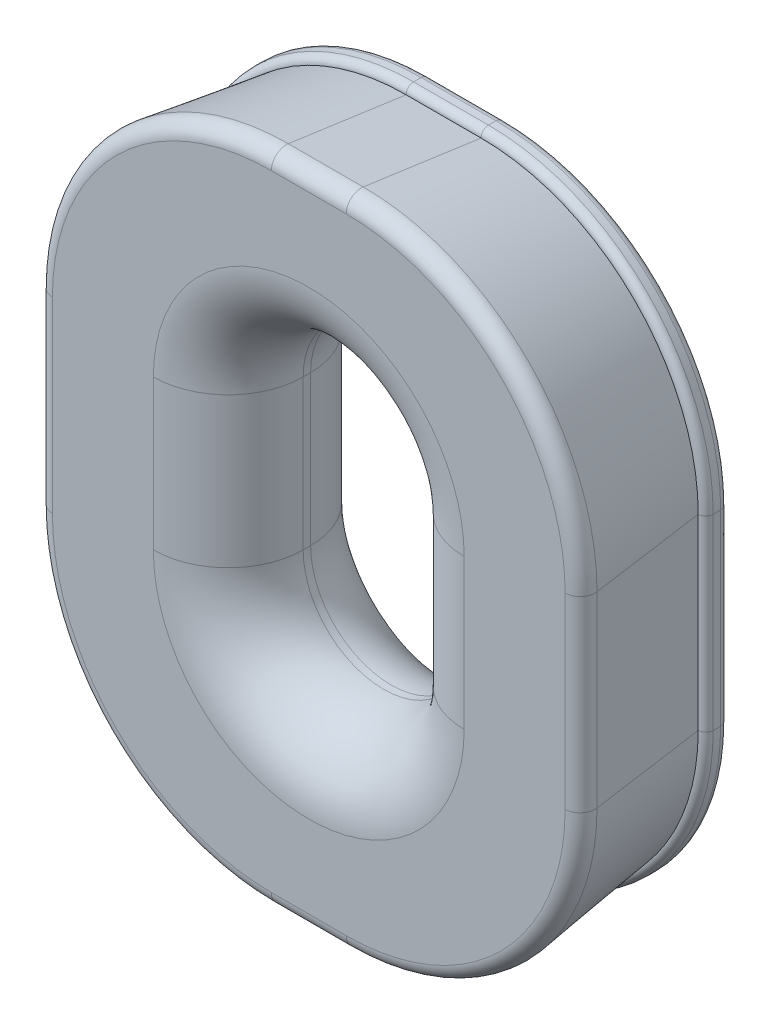
SolidWorks part; units mm, degrees
ref_plane "Front Plane" through (0, 0, 0) normal (0, 0, 1) x (1, 0, 0)
ref_plane "Top Plane" through (0, 0, 0) normal (0, 1, 0) x (1, 0, 0)
ref_plane "Right Plane" through (0, 0, 0) normal (1, 0, 0) x (0, 0, -1)
sketch "Sketch2" plane through (0, 0, 0) normal (0, 0, 1) x (1, 0, 0)
  line L1 (-5, -42.5) -> (5, -42.5)
  line L2 (-35, -12.5) -> (-35, 12.5)
  line L3 (-5, 42.5) -> (5, 42.5)
  line L4 (35, -12.5) -> (35, 12.5)
  line L5 (-35, -42.5) -> (35, 42.5) construction
  line L6 (-35, 42.5) -> (35, -42.5) construction
  arc A0 (-35, 12.5) -> (-5, 42.5) centre (-5, 12.5) cw
  arc A1 (-5, -42.5) -> (-35, -12.5) centre (-5, -12.5) cw
  arc A2 (5, -42.5) -> (35, -12.5) centre (5, -12.5) ccw
  arc A3 (5, 42.5) -> (35, 12.5) centre (5, 12.5) cw
  point P0 (0, 0)
  dimension "D1" = 30
  dimension "D2" = 30
extrude "Boss-Extrude1" add sketch "Sketch2" along normal blind 3
fillet "Fillet1" radius 1 16 edges at (-26.2132, 33.7132, 3) (0, 42.5, 3) (26.2132, 33.7132, 3) (35, 0, 3) (26.2132, -33.7132, 3) (0, -42.5, 3) (-26.2132, -33.7132, 3) (-26.2132, 33.7132, 0) (0, 42.5, 0) (26.2132, 33.7132, 0) (35, 0, 0) (26.2132, -33.7132, 0) (0, -42.5, 0) (-26.2132, -33.7132, 0) (-35, 0, 3) (-35, 0, 0)
sketch "Sketch3" plane through (0, 0, 3) normal (0, 0, 1) x (1, 0, 0)
  line L4 (5, 41.5) -> (-5, 41.5)
  line L5 (-34, 12.5) -> (-34, -12.5)
  line L6 (-5, -41.5) -> (5, -41.5)
  line L7 (34, -12.5) -> (34, 12.5)
  line L8 (5, 41.5) -> (-5, 41.5)
  line L9 (-34, 12.5) -> (-34, -12.5)
  line L10 (-5, -41.5) -> (5, -41.5)
  line L11 (34, -12.5) -> (34, 12.5)
  arc A4 (-5, 41.5) -> (-34, 12.5) centre (-5, 12.5) ccw
  arc A5 (-34, -12.5) -> (-5, -41.5) centre (-5, -12.5) ccw
  arc A6 (5, -41.5) -> (34, -12.5) centre (5, -12.5) ccw
  arc A7 (34, 12.5) -> (5, 41.5) centre (5, 12.5) ccw
  arc A8 (-5, 41.5) -> (-34, 12.5) centre (-5, 12.5) ccw
  arc A9 (-34, -12.5) -> (-5, -41.5) centre (-5, -12.5) ccw
  arc A10 (5, -41.5) -> (34, -12.5) centre (5, -12.5) ccw
  arc A11 (34, 12.5) -> (5, 41.5) centre (5, 12.5) ccw
  dimension "D1" = 0
extrude "Boss-Extrude2" add sketch "Sketch3" along normal blind 18 draft 8 draft outward yes
fillet "Fillet2" radius 2 8 edges at (0, 44.0297, 21) (27.2949, 34.7949, 21) (36.5297, 0, 21) (27.2949, -34.7949, 21) (0, -44.0297, 21) (-27.2949, -34.7949, 21) (-36.5297, 0, 21) (-27.2949, 34.7949, 21)
sketch "Sketch5" plane through (0, 0, 21) normal (0, 0, 1) x (1, 0, 0)
  line L0 (0, -10) -> (0, 10) construction
  line L2 (-10.7521, -10) -> (-10.7521, 10)
  line L3 (10.7521, -10) -> (10.7521, 10)
  arc A0 (-10.7521, -10) -> (10.7521, -10) centre (0, -10) ccw
  arc A1 (10.7521, 10) -> (-10.7521, 10) centre (0, 10) ccw
  point P5 (0, 0)
  dimension "D1" = 20
extrude "Cut-Extrude1" cut sketch "Sketch5" against normal through all
fillet "Fillet4" radius 10 8 edges at (0, 20.7521, 21) (10.7521, 0, 21) (0, -20.7521, 21) (-10.7521, 0, 21) (-10.7521, 0, 0) (0, 20.7521, 0) (10.7521, 0, 0) (0, -20.7521, 0)
